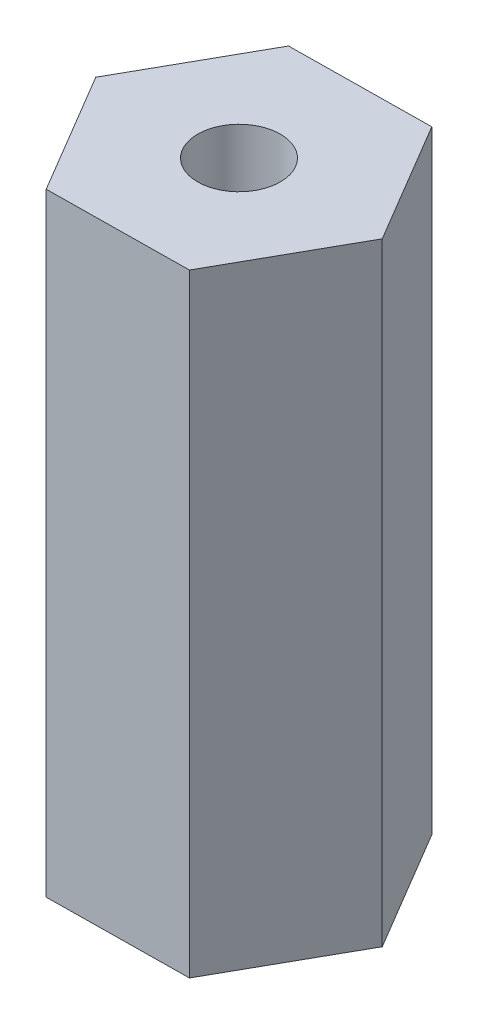
SolidWorks part; units mm, degrees
ref_plane "Alzado" through (0, 0, 0) normal (0, 0, 1) x (1, 0, 0)
ref_plane "Planta" through (0, 0, 0) normal (0, 1, 0) x (1, 0, 0)
ref_plane "Vista lateral" through (0, 0, 0) normal (1, 0, 0) x (0, 0, -1)
sketch "Croquis1" plane through (0, 0, 0) normal (0, 1, 0) x (1, 0, 0)
  line L1 (3.5343, -5.9589) -> (6.9277, 0.0814)
  line L2 (6.9277, 0.0814) -> (3.3934, 6.0403)
  line L3 (3.3934, 6.0403) -> (-3.5343, 5.9589)
  line L4 (-3.5343, 5.9589) -> (-6.9277, -0.0814)
  line L5 (-6.9277, -0.0814) -> (-3.3934, -6.0403)
  line L6 (-3.3934, -6.0403) -> (3.5343, -5.9589)
  circle A0 centre (0, 0) radius 6 construction
  dimension "D1" = 12
extrude "Saliente-Extruir1" add sketch "Croquis1" along normal blind 30
sketch "Croquis2" plane through (0, 30, 0) normal (0, 1, 0) x (1, 0, 0)
  circle A0 centre (0, 0) radius 2.025
  dimension "D1" = 4.05
extrude "Cortar-Extruir1" cut sketch "Croquis2" against normal blind 18
